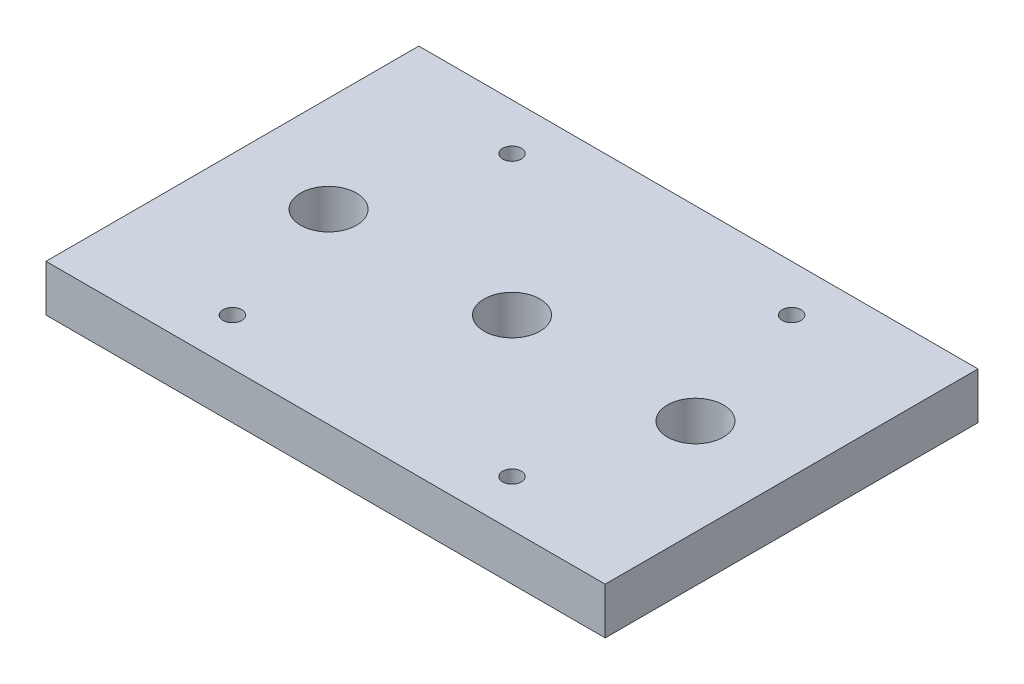
SolidWorks part; units mm, degrees
ref_plane "Front Plane" through (0, 0, 0) normal (0, 0, 1) x (1, 0, 0)
ref_plane "Top Plane" through (0, 0, 0) normal (0, 1, 0) x (1, 0, 0)
ref_plane "Right Plane" through (0, 0, 0) normal (1, 0, 0) x (0, 0, -1)
sketch "Sketch1" plane through (0, 0, 0) normal (0, 1, 0) x (1, 0, 0)
  line L1 (-76.2, -50.8) -> (76.2, -50.8)
  line L2 (-76.2, -50.8) -> (-76.2, 50.8)
  line L3 (-76.2, 50.8) -> (76.2, 50.8)
  line L4 (76.2, -50.8) -> (76.2, 50.8)
  line L5 (-76.2, -50.8) -> (76.2, 50.8) construction
  line L6 (-76.2, 50.8) -> (76.2, -50.8) construction
  point P0 (0, 0)
  dimension "D1" = 152.4
  dimension "D2" = 101.6
extrude "Boss-Extrude1" add sketch "Sketch1" along normal blind 12.7
hole_wizard "CBORE for 3/8 Hex Head Bolt1" positions "Sketch2" profile "Sketch3" counterbore size "3/8" standard "ANSI Inch" end condition through all
sketch "Sketch2" plane through (0, 12.7, 0) normal (0, 1, 0) x (1, 0, 0)
  line L1 (-76.2, 0) -> (76.2, 0) construction
  line L2 (-76.2, 50.8) -> (-76.2, -50.8) construction
  line L3 (76.2, -50.8) -> (76.2, 50.8) construction
  point P0 (-50, 0)
  point P2 (50, 0)
  point P4 (0, 0)
  dimension "D1" = 50
  dimension "D2" = 50
sketch "Sketch3" plane through (-50, 12.7, 0) normal (1, 0, 0) x (0, 0, 1)
  line L0 (0, 0) -> (0, 12.7)
  line L1 (0, 12.7) -> (5.0419, 12.7)
  line L3 (5.0419, 12.7) -> (5.0419, 11.176)
  line L4 (5.0419, 11.176) -> (7.62, 11.176)
  line L5 (7.62, 11.176) -> (7.62, 0)
  line L7 (7.62, 0) -> (0, 0)
  line L11 (0, -6.35) -> (0, 107.95) construction
  dimension "Thru Hole Dia." = 10.0838
  dimension "Thru Hole Depth" = 12.7
  dimension "C'Bore Dia." = 15.24
  dimension "C'Bore Depth" = 11.176
hole_wizard "Tap Drill for 1/4-20 Tap1" positions "Sketch4" profile "Sketch5" hole size "1/4-20" standard "ANSI Inch" end condition through all
sketch "Sketch4" plane through (0, 0, 0) normal (0, 1, 0) x (1, 0, 0)
  point P6 (-38.1, 38.1)
  point P33 (38.1, 38.1)
  point P34 (38.1, -38.1)
  point P35 (-38.1, -38.1)
  dimension "D1" = 38.1
  dimension "D2" = 38.1
  dimension "D3" = 2
  dimension "D4" = 2
sketch "Sketch5" plane through (-38.1, 0, -38.1) normal (1, 0, 0) x (0, 0, -1)
  line L0 (0, 0) -> (0, 12.7)
  line L1 (0, 12.7) -> (2.5527, 12.7)
  line L2 (2.5527, 12.7) -> (2.5527, 0)
  line L5 (2.5527, 0) -> (0, 0)
  line L11 (0, -6.35) -> (0, 107.95) construction
  dimension "Thru Hole Dia." = 5.1054
  dimension "Thru Hole Depth" = 12.7
